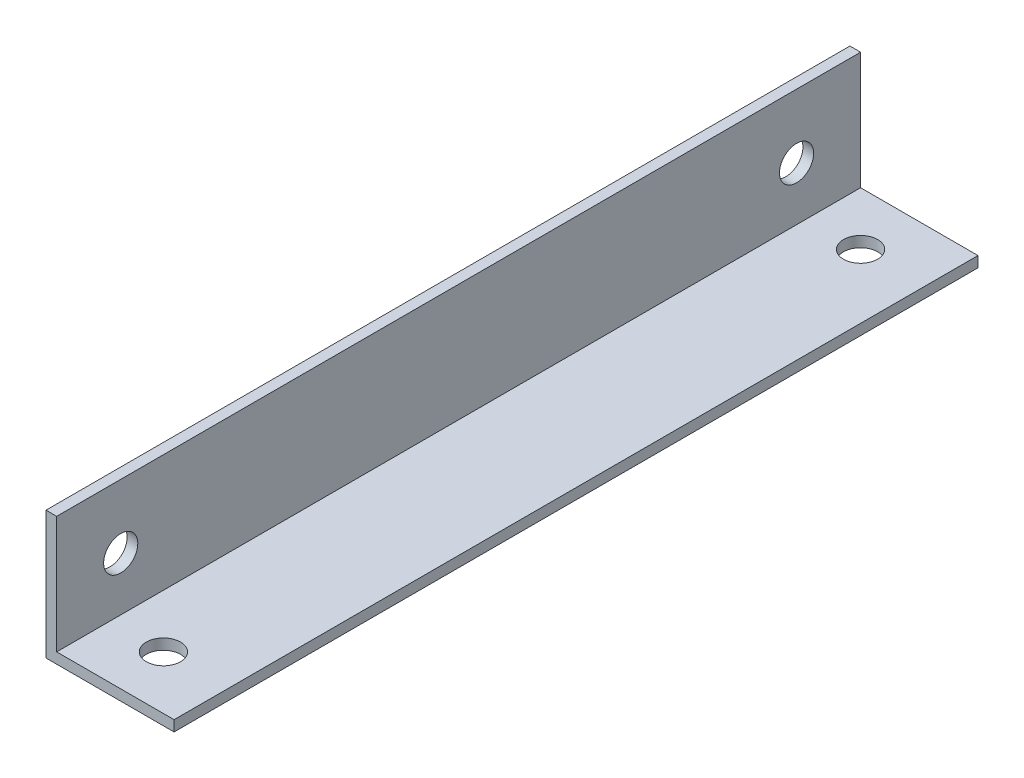
SolidWorks part; units mm, degrees
ref_plane "Front Plane" through (0, 0, 0) normal (0, 0, 1) x (1, 0, 0)
ref_plane "Top Plane" through (0, 0, 0) normal (0, 1, 0) x (1, 0, 0)
ref_plane "Right Plane" through (0, 0, 0) normal (1, 0, 0) x (0, 0, -1)
sketch "Sketch1" plane through (0, 0, 0) normal (0, 0, 1) x (1, 0, 0)
  line L0 (0, 0) -> (0, 30)
  line L1 (0, 30) -> (2.5, 30)
  line L2 (2.5, 30) -> (2.5, 2.5)
  line L3 (2.5, 2.5) -> (30, 2.5)
  line L4 (30, 2.5) -> (30, 0)
  line L5 (30, 0) -> (0, 0)
  dimension "D1" = 2.5
  dimension "D2" = 2.5
  dimension "D3" = 30
  dimension "D4" = 30
extrude "Boss-Extrude1" add sketch "Sketch1" along normal blind 188.3
sketch "Sketch2" plane through (0, 2.5, 0) normal (0, 1, 0) x (1, 0, 0)
  line L0 (-50.0143, -94.15) -> (67.7484, -94.15) construction
  line L1 (30, 0) -> (2.5, 0) construction
  line L2 (30, -188.3) -> (30, 0) construction
  circle A0 centre (15, -12.5) radius 4
  circle A1 centre (15, -175.8) radius 4
  dimension "D4" = 8
  dimension "D1" = 94.15
  dimension "D2" = 15
  dimension "D3" = 12.5
extrude "Cut-Extrude1" cut sketch "Sketch2" against normal through all
sketch "Sketch3" plane through (2.5, 0, 0) normal (1, 0, 0) x (0, 0, -1)
  line L0 (-94.15, 52.6979) -> (-94.15, -10.6912) construction
  line L1 (0, 2.5) -> (0, 30) construction
  line L2 (-188.3, 30) -> (0, 30) construction
  circle A0 centre (-15, 15) radius 4
  circle A1 centre (-173.3, 15) radius 4
  dimension "D4" = 8
  dimension "D1" = 94.15
  dimension "D2" = 15
  dimension "D3" = 15
extrude "Cut-Extrude2" cut sketch "Sketch3" against normal through all
